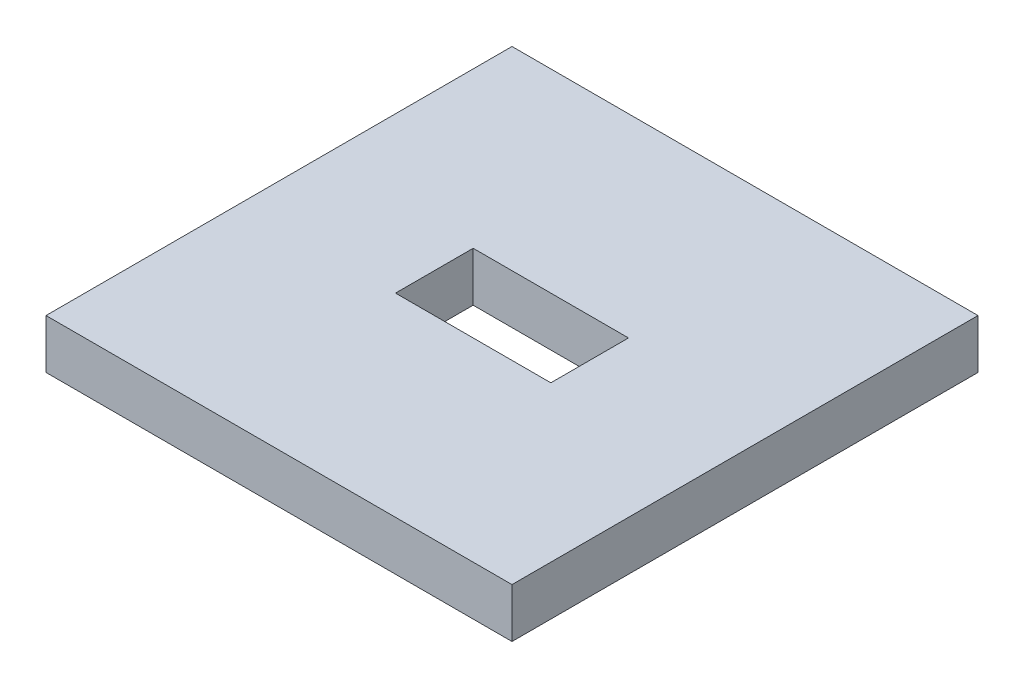
SolidWorks part; units mm, degrees
ref_plane "Front Plane" through (0, 0, 0) normal (0, 0, 1) x (1, 0, 0)
ref_plane "Top Plane" through (0, 0, 0) normal (0, 1, 0) x (1, 0, 0)
ref_plane "Right Plane" through (0, 0, 0) normal (1, 0, 0) x (0, 0, -1)
sketch "Sketch1" plane through (0, 0, 0) normal (0, 1, 0) x (1, 0, 0)
  line L1 (0, 0) -> (60, 0)
  line L2 (0, 0) -> (0, 60)
  line L3 (0, 60) -> (60, 60)
  line L4 (60, 0) -> (60, 60)
  line L5 (20, 35) -> (40, 35)
  line L6 (20, 35) -> (20, 25)
  line L7 (20, 25) -> (40, 25)
  line L8 (40, 35) -> (40, 25)
  dimension "D1" = 60
  dimension "D2" = 60
  dimension "D3" = 20
  dimension "D4" = 10
  dimension "D5" = 20
  dimension "D6" = 25
extrude "Boss-Extrude1" add sketch "Sketch1" along normal blind 6.35
